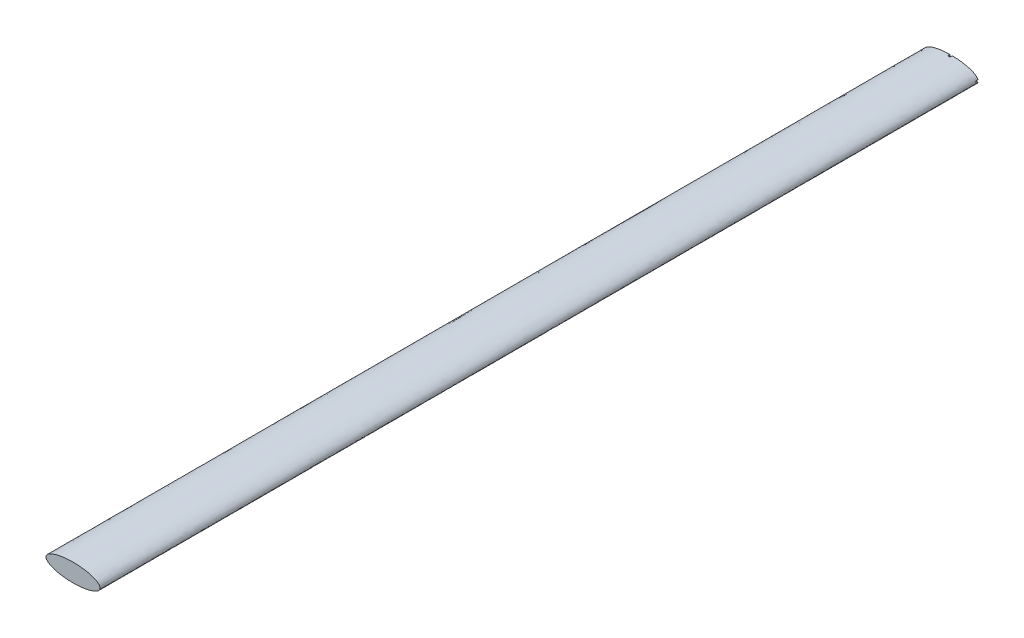
SolidWorks part; units mm, degrees
material "Eau"
ref_plane "Plan de face" through (0, 0, 0) normal (0, 0, 1) x (1, 0, 0)
ref_plane "Plan de dessus" through (0, 0, 0) normal (0, 1, 0) x (1, 0, 0)
ref_plane "Plan de droite" through (0, 0, 0) normal (1, 0, 0) x (0, 0, -1)
sketch "Esquisse1" plane through (0, 0, 0) normal (0, 0, 1) x (1, 0, 0)
  ellipse E0 centre (0, 0) end of major axis (-12, 0) minor radius 4
  dimension "D1" = 12
  dimension "D2" = 4
  dimension "D3" = 8
  dimension "D4" = 24
extrude "Boss.-Extru.1" add sketch "Esquisse1" along normal blind 390
sketch "Esquisse2" plane through (0, 0, 0) normal (0, 0, -1) x (-1, 0, 0)
  line L0 (0.5, -0.5) -> (0.5, -5.0527)
  line L1 (-12.4063, 0.5) -> (-0.5, 0.5)
  line L2 (-12.4063, 0.5) -> (-12.4063, -0.5)
  line L3 (-12.4063, -0.5) -> (-0.5, -0.5)
  line L4 (12.2707, 0.5) -> (12.2707, -0.5)
  line L5 (-0.5, 4.9235) -> (0.5, 4.9235)
  line L6 (-0.5, 4.9235) -> (-0.5, 0.5)
  line L7 (-0.5, -5.0527) -> (0.5, -5.0527)
  line L8 (0.5, 4.9235) -> (0.5, 0.5)
  line L9 (0.5, 0.5) -> (12.2707, 0.5)
  line L10 (-0.5, -0.5) -> (-0.5, -5.0527)
  line L11 (0.5, -0.5) -> (12.2707, -0.5)
  dimension "D1" = 1
  dimension "D2" = 0.5
  dimension "D3" = 0.5
extrude "Enlèv. mat.-Extru.1" cut sketch "Esquisse2" against normal blind 1
